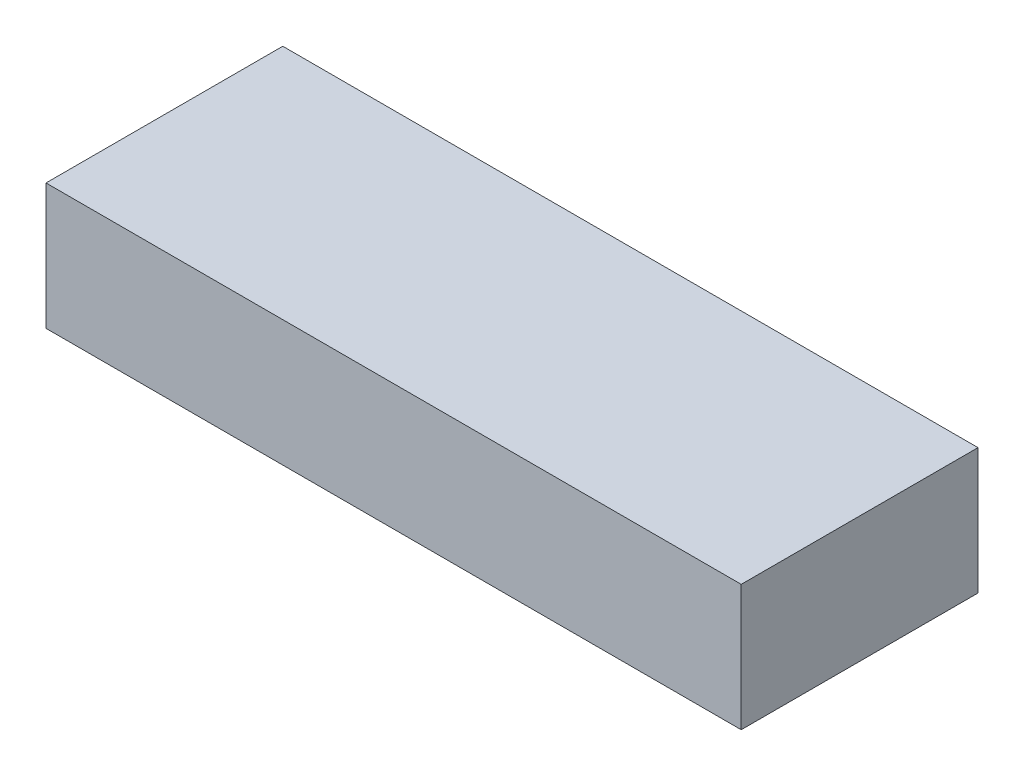
SolidWorks part; units mm, degrees
ref_plane "Front Plane" through (0, 0, 0) normal (0, 0, 1) x (1, 0, 0)
ref_plane "Top Plane" through (0, 0, 0) normal (0, 1, 0) x (1, 0, 0)
ref_plane "Right Plane" through (0, 0, 0) normal (1, 0, 0) x (0, 0, -1)
sketch "Sketch1" plane through (0, 0, 0) normal (0, 1, 0) x (1, 0, 0)
  line L1 (0, 0) -> (138, 0)
  line L2 (0, 0) -> (0, 47)
  line L3 (0, 47) -> (138, 47)
  line L4 (138, 0) -> (138, 47)
  dimension "D1" = 138
  dimension "D2" = 47
extrude "Boss-Extrude1" add sketch "Sketch1" along normal blind 25
